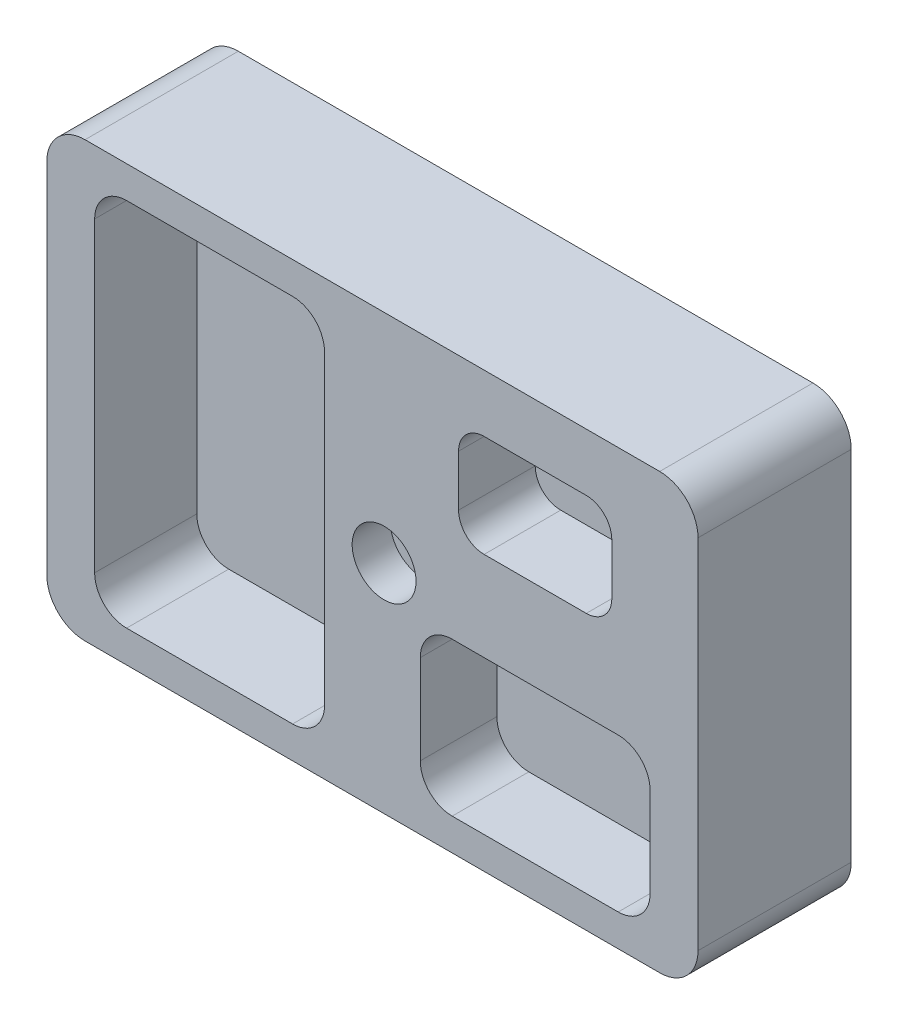
SolidWorks part; units mm, degrees
ref_plane "Front Plane" through (0, 0, 0) normal (0, 0, 1) x (1, 0, 0)
ref_plane "Top Plane" through (0, 0, 0) normal (0, 1, 0) x (1, 0, 0)
ref_plane "Right Plane" through (0, 0, 0) normal (1, 0, 0) x (0, 0, -1)
sketch "Sketch1" plane through (0, 0, 0) normal (0, 0, 1) x (1, 0, 0)
  line L1 (-80.9625, 53.975) -> (80.9625, 53.975)
  line L2 (-80.9625, 53.975) -> (-80.9625, -53.975)
  line L3 (-80.9625, -53.975) -> (80.9625, -53.975)
  line L4 (80.9625, 53.975) -> (80.9625, -53.975)
  line L5 (-80.9625, 53.975) -> (80.9625, -53.975) construction
  line L6 (-80.9625, -53.975) -> (80.9625, 53.975) construction
  point P0 (0, 0)
  dimension "D1" = 161.925
  dimension "D2" = 107.95
extrude "Boss-Extrude1" add sketch "Sketch1" against normal blind 38.1
sketch "Sketch2" plane through (0, 0, 0) normal (0, 0, 1) x (1, 0, 0)
  line L0 (0, 0) -> (-80.9625, 0) construction
  line L1 (-69.0562, -46.0375) -> (-11.9062, -46.0375)
  line L2 (-69.0562, -46.0375) -> (-69.0562, 46.0375)
  line L3 (-69.0562, 46.0375) -> (-11.9062, 46.0375)
  line L4 (-11.9062, -46.0375) -> (-11.9062, 46.0375)
  line L5 (-69.0562, -46.0375) -> (-11.9062, 46.0375) construction
  line L6 (-69.0562, 46.0375) -> (-11.9062, -46.0375) construction
  line L7 (-80.9625, 53.975) -> (-80.9625, -53.975) construction
  point P0 (0, 0)
  point P10 (-40.4812, 0)
  point P11 (-40.4812, 0)
  dimension "D1" = 57.15
  dimension "D2" = 92.075
extrude "Cut-Extrude1" cut sketch "Sketch2" against normal blind 25.4
fillet "Fillet1" radius 7.9375 4 edges at (-11.9062, -46.0375, -12.7) (-69.0562, -46.0375, -12.7) (-69.0562, 46.0375, -12.7) (-11.9062, 46.0375, -12.7)
sketch "Sketch3" plane through (0, 0, 0) normal (0, 0, 1) x (1, 0, 0)
  line L0 (0, 53.975) -> (0, -53.975) construction
  line L1 (80.9625, 53.975) -> (-80.9625, 53.975) construction
  line L2 (-80.9625, -53.975) -> (80.9625, -53.975) construction
  line L3 (0, 0) -> (80.9625, 0) construction
  line L4 (80.9625, -53.975) -> (80.9625, 53.975) construction
  line L5 (40.4813, 0) -> (40.4813, 53.975) construction
  line L6 (11.9062, -46.0375) -> (69.0562, -46.0375)
  line L7 (11.9062, -46.0375) -> (11.9062, -7.9375)
  line L8 (11.9062, -7.9375) -> (69.0562, -7.9375)
  line L9 (69.0562, -46.0375) -> (69.0562, -7.9375)
  line L10 (11.9062, -46.0375) -> (69.0562, -7.9375) construction
  line L11 (11.9062, -7.9375) -> (69.0562, -46.0375) construction
  line L12 (21.4312, 14.2875) -> (59.5312, 14.2875)
  line L13 (21.4312, 14.2875) -> (21.4312, 39.6875)
  line L14 (21.4312, 39.6875) -> (59.5312, 39.6875)
  line L15 (59.5312, 14.2875) -> (59.5312, 39.6875)
  line L16 (21.4312, 14.2875) -> (59.5312, 39.6875) construction
  line L17 (21.4312, 39.6875) -> (59.5312, 14.2875) construction
  line L18 (40.4813, 26.9875) -> (80.9625, 26.9875) construction
  line L19 (40.4813, 0) -> (40.4813, -53.975) construction
  line L20 (40.4813, -26.9875) -> (80.9625, -26.9875) construction
  point P11 (40.4812, -26.9875)
  point P18 (40.4812, 26.9875)
  dimension "D1" = 38.1
  dimension "D2" = 25.4
  dimension "D3" = 57.15
  dimension "D4" = 38.1
extrude "Cut-Extrude2" cut sketch "Sketch3" against normal blind 19.05
fillet "Fillet2" radius 6.35 4 edges at (59.5312, 14.2875, -9.525) (21.4312, 14.2875, -9.525) (59.5312, 39.6875, -9.525) (21.4312, 39.6875, -9.525)
fillet "Fillet3" radius 7.9375 4 edges at (11.9062, -46.0375, -9.525) (69.0562, -46.0375, -9.525) (69.0562, -7.9375, -9.525) (11.9062, -7.9375, -9.525)
fillet "Fillet4" radius 9.525 4 edges at (-80.9625, 53.975, -19.05) (80.9625, 53.975, -19.05) (80.9625, -53.975, -19.05) (-80.9625, -53.975, -19.05)
hole_wizard "CBORE for 3/8 Socket Head Cap Screw1" positions "Sketch6" profile "Sketch5" counterbore size "3/8" standard "ANSI Inch" end condition through all
sketch "Sketch6" plane through (0, 0, 0) normal (0, 0, 1) x (1, 0, 0)
  point P0 (2.9103, 0)
sketch "Sketch5" plane through (2.9103, 0, 0) normal (1, 0, 0) x (0, -1, 0)
  line L0 (0, 0) -> (0, 38.1)
  line L1 (0, 38.1) -> (5.0419, 38.1)
  line L3 (5.0419, 38.1) -> (5.0419, 9.525)
  line L4 (5.0419, 9.525) -> (7.9375, 9.525)
  line L5 (7.9375, 9.525) -> (7.9375, 0)
  line L7 (7.9375, 0) -> (0, 0)
  line L11 (0, -6.35) -> (0, 107.95) construction
  dimension "Thru Hole Dia." = 10.0838
  dimension "Thru Hole Depth" = 38.1
  dimension "C'Bore Dia." = 15.875
  dimension "C'Bore Depth" = 9.525
